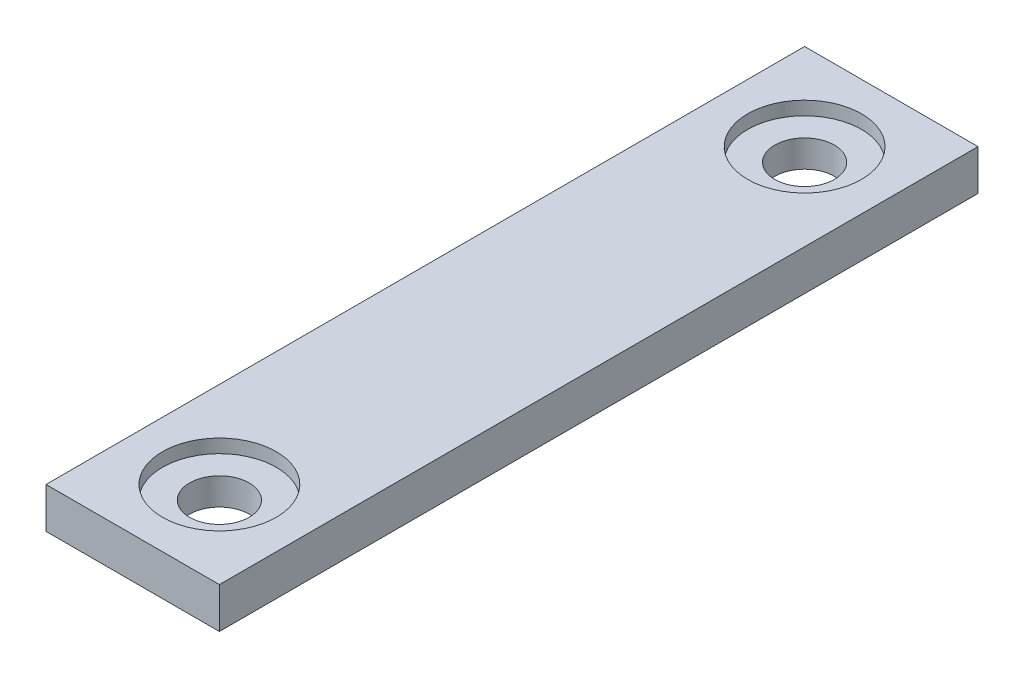
SolidWorks part; units mm, degrees
material "PLA"
ref_plane "Спереди" through (0, 0, 0) normal (0, 0, 1) x (1, 0, 0)
ref_plane "Сверху" through (0, 0, 0) normal (0, 1, 0) x (1, 0, 0)
ref_plane "Справа" through (0, 0, 0) normal (1, 0, 0) x (0, 0, -1)
sketch "Эскиз1" plane through (0, 0, 0) normal (0, 1, 0) x (1, 0, 0)
  line L1 (3.2, 14) -> (-3.2, 14)
  line L2 (3.2, 14) -> (3.2, -14)
  line L3 (3.2, -14) -> (-3.2, -14)
  line L4 (-3.2, 14) -> (-3.2, -14)
  line L5 (3.2, 14) -> (-3.2, -14) construction
  line L6 (3.2, -14) -> (-3.2, 14) construction
  point P0 (0, 0)
  dimension "D1" = 6.4
  dimension "D2" = 28
extrude "Бобышка-Вытянуть1" add sketch "Эскиз1" along normal blind 1.5
sketch "Эскиз2" plane through (0, 1.5, 0) normal (0, 1, 0) x (1, 0, 0)
  line L0 (0, 0) -> (0, 50000) construction
  line L1 (0, 0) -> (-50000, 0) construction
  circle A0 centre (0, 10.8) radius 1.1
  circle A1 centre (0, -10.8) radius 1.1
  dimension "D1" = 2.2
  dimension "D2" = 21.6
extrude "Вырез-Вытянуть1" cut sketch "Эскиз2" against normal through all
sketch "Эскиз3" plane through (0, 1.5, 0) normal (0, 1, 0) x (1, 0, 0)
  circle A0 centre (0, 10.8) radius 2.1
  circle A1 centre (0, -10.8) radius 2.1
  dimension "D1" = 4.2
extrude "Вырез-Вытянуть2" cut sketch "Эскиз3" against normal blind 0.5
